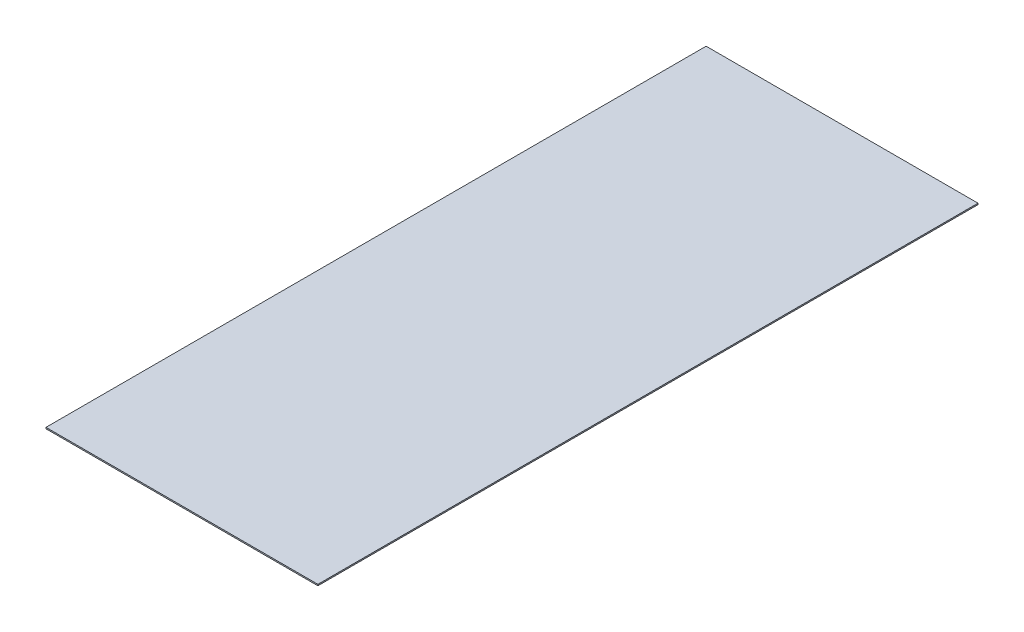
SolidWorks part; units mm, degrees
ref_plane "Plano frontal" through (0, 0, 0) normal (0, 0, 1) x (1, 0, 0)
ref_plane "Plano superior" through (0, 0, 0) normal (0, 1, 0) x (1, 0, 0)
ref_plane "Plano direito" through (0, 0, 0) normal (1, 0, 0) x (0, 0, -1)
sketch "Esboço1" plane through (0, 0, 0) normal (0, 0, 1) x (1, 0, 0)
  line L0 (208, 1) -> (-208, -1) construction
  line L1 (-208, 1) -> (208, 1)
  line L2 (-208, 1) -> (-208, -1)
  line L3 (-208, -1) -> (208, -1)
  line L4 (208, 1) -> (208, -1)
  dimension "D1" = 416
  dimension "D2" = 2
extrude "Ressalto-extrusão1" add sketch "Esboço1" along normal blind 1010
